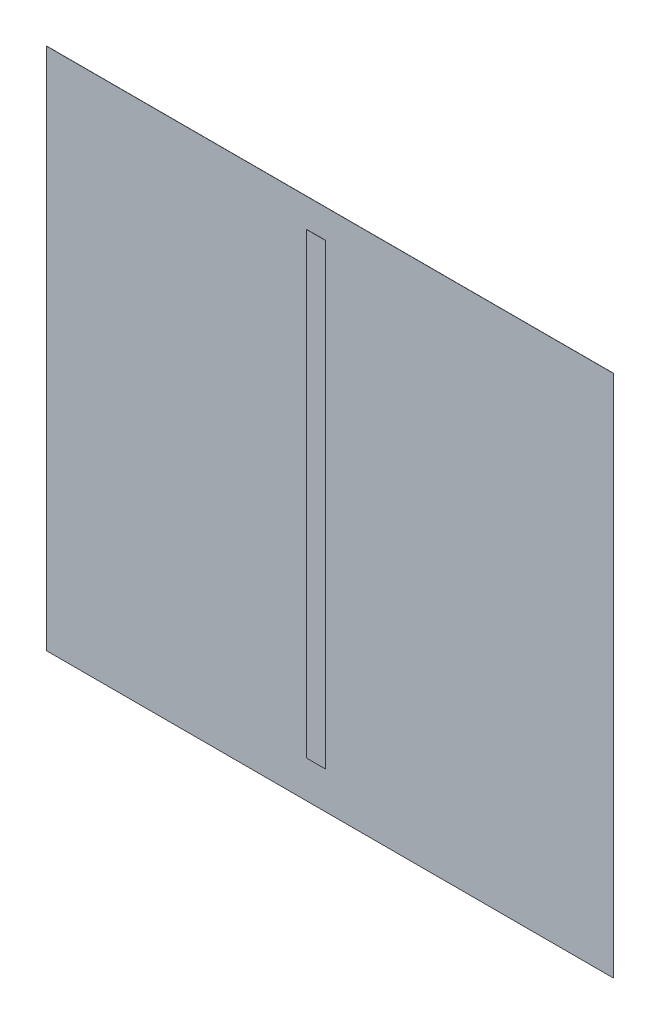
SolidWorks part; units mm, degrees
ref_plane "Спереди" through (0, 0, 0) normal (0, 0, 1) x (1, 0, 0)
ref_plane "Сверху" through (0, 0, 0) normal (0, 1, 0) x (1, 0, 0)
ref_plane "Справа" through (0, 0, 0) normal (1, 0, 0) x (0, 0, -1)
sketch "Эскиз2" plane through (0, 0, 0) normal (0, 0, 1) x (1, 0, 0)
  line L0 (0, 32.5302) -> (0, -67.4698)
  line L5 (0, -67.4698) -> (4.098, -67.4698)
  line L6 (4.098, -67.4698) -> (4.098, 32.5302)
  line L7 (4.098, 32.5302) -> (0, 32.5302)
extrude "Бобышка-Вытянуть1" add sketch "Эскиз2" along normal blind 0.035 contours L6 L7 L0 L5
sketch "Эскиз6" plane through (0, 0, -1) normal (0, 0, -1) x (-1, 0, 0)
  line L5 (-65.9417, 37.7958) -> (57.8796, 37.7958)
  line L6 (-65.9417, 37.7958) -> (-65.9417, -76.6008)
  line L7 (-65.9417, -76.6008) -> (57.8796, -76.6008)
  line L8 (57.8796, 37.7958) -> (57.8796, -76.6008)
  point P0 (-2.1264, -7.7411)
extrude "Бобышка-Вытянуть4" add sketch "Эскиз6" along normal blind 0.035
